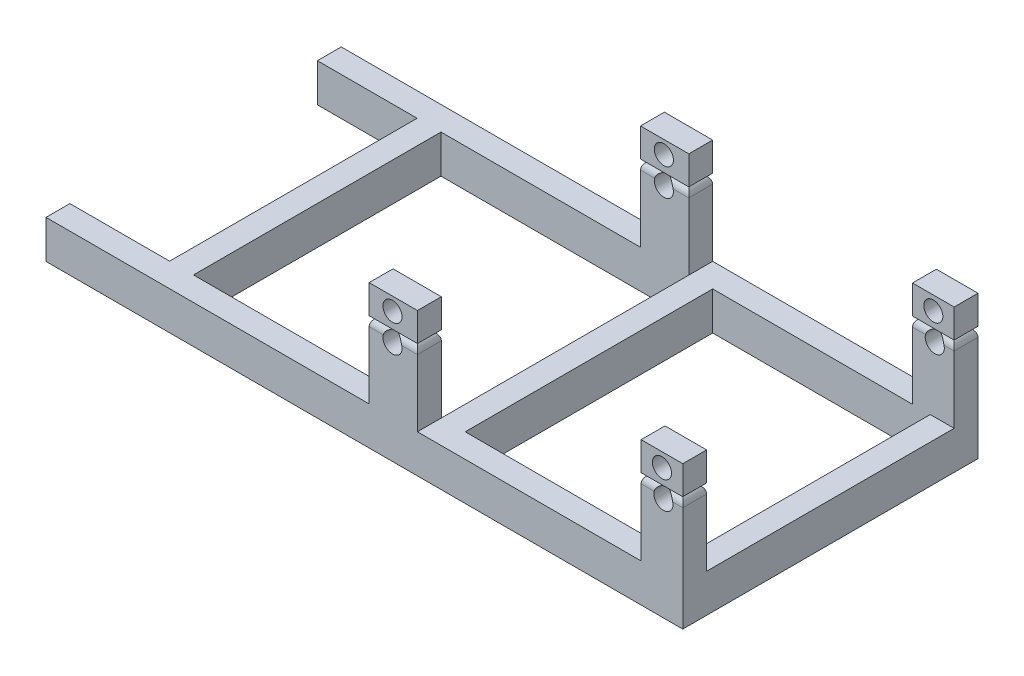
SolidWorks part; units mm, degrees
ref_plane "Front Plane" through (0, 0, 0) normal (0, 0, 1) x (1, 0, 0)
ref_plane "Top Plane" through (0, 0, 0) normal (0, 1, 0) x (1, 0, 0)
ref_plane "Right Plane" through (0, 0, 0) normal (1, 0, 0) x (0, 0, -1)
sketch "Sketch1" plane through (0, 0, 0) normal (0, 1, 0) x (1, 0, 0)
  line L0 (137.3897, -28.7596) -> (656.3431, -28.7596)
  line L1 (-121.4569, 21.2404) -> (1211.9431, 21.2404)
  line L2 (-121.4569, 21.2404) -> (-121.4569, -28.7596)
  line L3 (-121.4569, -28.7596) -> (87.3897, -28.7596)
  line L4 (1211.9431, 21.2404) -> (1211.9431, -50.701)
  line L5 (-121.4569, -547.0087) -> (87.3897, -547.0087)
  line L6 (-121.4569, -547.0087) -> (-121.4569, -597.0087)
  line L7 (-121.4569, -597.0087) -> (1211.9431, -597.0087)
  line L8 (1211.9431, -568.9502) -> (1211.9431, -597.0087)
  line L10 (137.3897, -28.7596) -> (137.3897, -547.0087)
  line L12 (87.3897, -28.7596) -> (87.3897, -547.0087)
  line L14 (656.3431, -28.7596) -> (656.3431, -547.0087)
  line L16 (706.3431, -28.7596) -> (706.3431, -547.0087)
  line L17 (137.3897, -547.0087) -> (656.3431, -547.0087)
  line L19 (1211.9431, -50.701) -> (1211.9431, -568.9502)
  line L21 (1161.9431, -28.7596) -> (1161.9431, -547.0087)
  line L22 (706.3431, -547.0087) -> (1161.9431, -547.0087)
  line L23 (706.3431, -28.7596) -> (1161.9431, -28.7596)
  dimension "D1" = 1333.4
  dimension "D2" = 50
  dimension "D3" = 50
  dimension "D4" = 50
  dimension "D5" = 50
  dimension "D6" = 50
extrude "Boss-Extrude3" add sketch "Sketch1" along normal blind 80
sketch "Sketch2" plane through (0, 80, 0) normal (0, 1, 0) x (1, 0, 0)
  line L0 (1211.9431, 21.2404) -> (-121.4569, 21.2404) construction
  line L1 (555.2113, 21.2404) -> (656.3431, 21.2404)
  line L2 (555.2113, 21.2404) -> (555.2113, -28.7596)
  line L3 (555.2113, -28.7596) -> (656.3431, -28.7596)
  line L4 (656.3431, 21.2404) -> (656.3431, -28.7596)
  line L5 (-121.4569, -597.0087) -> (1211.9431, -597.0087) construction
  line L6 (706.3431, -547.0087) -> (1161.9431, -547.0087) construction
  line L7 (1124.7895, 21.2404) -> (1211.9431, 21.2404)
  line L8 (656.3431, -547.0087) -> (555.2113, -547.0087)
  line L9 (656.3431, -547.0087) -> (656.3431, -597.0087)
  line L10 (656.3431, -597.0087) -> (555.2113, -597.0087)
  line L11 (555.2113, -547.0087) -> (555.2113, -597.0087)
  line L12 (1124.7895, 21.2404) -> (1124.7895, -28.7596)
  line L13 (1124.7895, -28.7596) -> (1211.9431, -28.7596)
  line L14 (1211.9431, 21.2404) -> (1211.9431, -28.7596)
  line L15 (1124.7895, -547.0087) -> (1211.9431, -547.0087)
  line L16 (1124.7895, -547.0087) -> (1124.7895, -597.0087)
  line L17 (1124.7895, -597.0087) -> (1211.9431, -597.0087)
  line L18 (1211.9431, -547.0087) -> (1211.9431, -597.0087)
extrude "Boss-Extrude4" add sketch "Sketch2" along normal blind 160
sketch "Sketch3" plane through (0, 0, -21.2404) normal (0, 0, -1) x (-1, 0, 0)
  line L0 (-656.3431, 240) -> (-555.2113, 240) construction
  circle A0 centre (-604.1193, 215.055) radius 20
  point P4 (-605.7772, 240)
  dimension "D1" = 25
sketch "Sketch4" plane through (0, 0, -21.2404) normal (0, 0, -1) x (-1, 0, 0)
  line L0 (-1211.9431, 240) -> (-1124.7895, 240) construction
  circle A0 centre (-1171.4004, 215.1848) radius 20
  point P4 (-1168.3663, 240)
  dimension "D1" = 25
fillet "Fillet1" radius 20 16 edges at (605.7772, 240, -21.2404) (656.3431, 240, 3.7596) (605.7772, 240, 28.7596) (555.2113, 240, 3.7596) (605.7772, 240, 597.0087) (555.2113, 240, 572.0087) (605.7772, 240, 547.0087) (656.3431, 240, 572.0087) (1168.3663, 240, -21.2404) (1211.9431, 240, 3.7596) (1168.3663, 240, 28.7596) (1124.7895, 240, 3.7596) (1168.3663, 240, 547.0087) (1211.9431, 240, 572.0087) (1168.3663, 240, 597.0087) (1124.7895, 240, 572.0087)
sketch "Sketch5" plane through (0, 0, 0) normal (0, -1, 0) x (-1, 0, 0)
  circle A0 centre (-1187.0469, -287.8841) radius 20
extrude "Cut-Extrude3" cut sketch "Sketch5" against normal blind 10 and the other way through all
extrude "Cut-Extrude4" cut sketch "Sketch3" against normal through all both and the other way through all contours A0
extrude "Cut-Extrude5" cut sketch "Sketch4" against normal through all both and the other way through all contours A0
sketch "Sketch6" plane through (0, 240, 0) normal (0, 1, 0) x (1, 0, 0)
  line L4 (656.3431, -597.0087) -> (636.3431, -577.0087) construction
  line L5 (555.2113, 21.2404) -> (656.3431, 21.2404)
  line L6 (555.2113, 21.2404) -> (555.2113, -28.7596)
  line L7 (555.2113, -28.7596) -> (656.3431, -28.7596)
  line L8 (656.3431, 21.2404) -> (656.3431, -28.7596)
  line L9 (555.2113, -547.0087) -> (656.3431, -547.0087)
  line L10 (555.2113, -547.0087) -> (555.2113, -597.0087)
  line L11 (555.2113, -597.0087) -> (656.3431, -597.0087)
  line L12 (656.3431, -547.0087) -> (656.3431, -597.0087)
extrude "Boss-Extrude5" add sketch "Sketch6" along normal blind 60
sketch "Sketch7" plane through (0, 0, 597.0087) normal (0, 0, 1) x (1, 0, 0)
  circle A0 centre (604.1193, 272.4192) radius 20
extrude "Cut-Extrude6" cut sketch "Sketch7" against normal through all both and the other way through all
sketch "Sketch8" plane through (0, 240, 0) normal (0, 1, 0) x (1, 0, 0)
  line L0 (1161.9431, -28.7596) -> (1211.9431, -28.7596) construction
  line L1 (1124.7895, -547.0087) -> (1211.9431, -547.0087)
  line L2 (1124.7895, -547.0087) -> (1124.7895, -597.0087)
  line L3 (1124.7895, -597.0087) -> (1211.9431, -597.0087)
  line L4 (1211.9431, -547.0087) -> (1211.9431, -597.0087)
  line L5 (1124.7895, 21.2404) -> (1211.9431, 21.2404)
  line L6 (1124.7895, 21.2404) -> (1124.7895, -28.7596)
  line L7 (1124.7895, -28.7596) -> (1211.9431, -28.7596)
  line L8 (1211.9431, 21.2404) -> (1211.9431, -28.7596)
  line L9 (1211.9431, 21.2404) -> (1211.9431, -28.7596) construction
extrude "Boss-Extrude6" add sketch "Sketch8" along normal blind 60
sketch "Sketch9" plane through (0, 0, 597.0087) normal (0, 0, 1) x (1, 0, 0)
  circle A0 centre (1168.3663, 271.004) radius 20
extrude "Cut-Extrude7" cut sketch "Sketch9" against normal through all both and the other way through all
